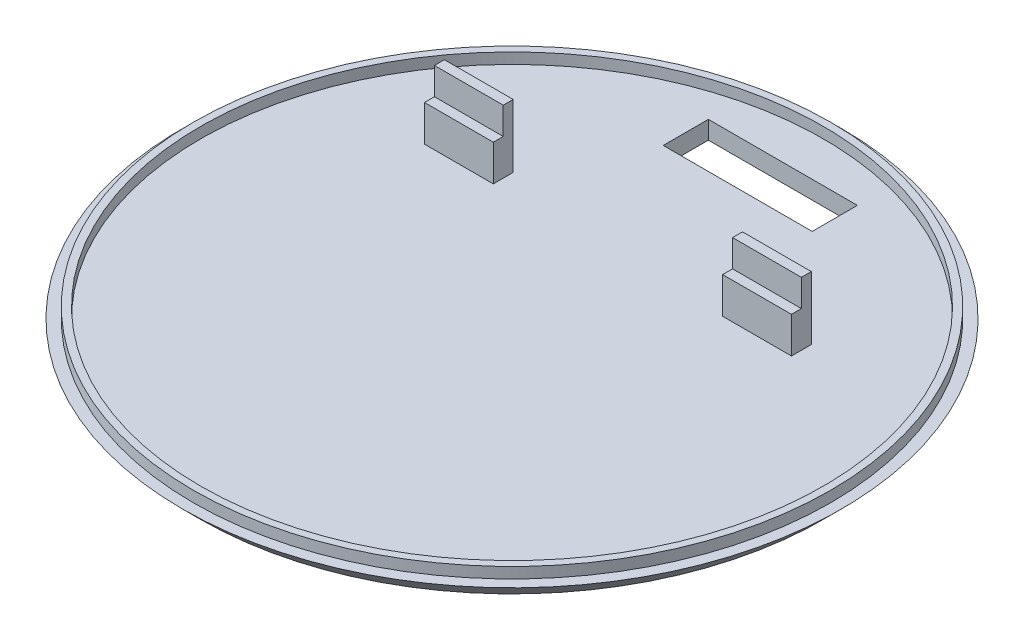
SolidWorks part; units mm, degrees
ref_plane "Front Plane" through (0, 0, 0) normal (0, 0, 1) x (1, 0, 0)
ref_plane "Top Plane" through (0, 0, 0) normal (0, 1, 0) x (1, 0, 0)
ref_plane "Right Plane" through (0, 0, 0) normal (1, 0, 0) x (0, 0, -1)
sketch "Sketch2" plane through (0, 0, 0) normal (0, 0, 1) x (1, 0, 0)
  line L0 (0, 31.7066) -> (0, -15.6367) construction
  line L1 (0, 0) -> (36.5, 0)
  line L2 (36.5, 0) -> (34.5, -2)
  line L3 (34.5, -2) -> (0, -2)
  line L4 (0, -2) -> (0, 0)
  line L6 (35.3, 0) -> (34.5, 0)
  line L7 (35.3, 0) -> (35.3, 1.2)
  line L8 (35.3, 1.2) -> (34.5, 1.2)
  line L9 (34.5, 0) -> (34.5, 1.2)
  dimension "D1" = 36.5
  dimension "D2" = 135
  dimension "D3" = 2
  dimension "D4" = 0.8
  dimension "D5" = 1.2
  dimension "D6" = 1.2
revolve "Revolve1" add sketch "Sketch2" angle 360 about L0
sketch "Sketch3" plane through (0, 0, 0) normal (0, 1, 0) x (1, 0, 0)
  line L1 (-8.25, 25) -> (8.25, 25)
  line L2 (-8.25, 25) -> (-8.25, 30)
  line L3 (-8.25, 30) -> (8.25, 30)
  line L4 (8.25, 25) -> (8.25, 30)
  dimension "D1" = 5
  dimension "D2" = 16.5
  dimension "D3" = 25
  dimension "D4" = 8.25
extrude "Cut-Extrude2" cut sketch "Sketch3" against normal up to next
sketch "Sketch4" plane through (0, 0, 0) normal (0, 1, 0) x (1, 0, 0)
  line L1 (-21.59, 14.1) -> (-13.97, 14.1)
  line L2 (-21.59, 14.1) -> (-21.59, 11.9)
  line L3 (-21.59, 11.9) -> (-13.97, 11.9)
  line L4 (-13.97, 14.1) -> (-13.97, 11.9)
  line L5 (11.43, 14.1) -> (19.05, 14.1)
  line L6 (11.43, 14.1) -> (11.43, 11.9)
  line L7 (11.43, 11.9) -> (19.05, 11.9)
  line L8 (19.05, 14.1) -> (19.05, 11.9)
  point P8 (15.24, 11.9)
  point P10 (-17.78, 11.9)
  point P11 (11.43, 13)
  dimension "D1" = 7.62
  dimension "D2" = 7.62
  dimension "D3" = 2.2
  dimension "D4" = 2.2
  dimension "D5" = 13
  dimension "D6" = 15.24
  dimension "D7" = 17.78
extrude "Boss-Extrude1" add sketch "Sketch4" along normal blind 4
sketch "Sketch5" plane through (0, 4, 0) normal (0, 1, 0) x (1, 0, 0)
  line L0 (-13.97, 11.9) -> (-13.97, 14.1) construction
  line L1 (-21.59, 14.1) -> (-13.97, 14.1)
  line L2 (-21.59, 14.1) -> (-21.59, 13)
  line L3 (-21.59, 13) -> (-13.97, 13)
  line L4 (-13.97, 14.1) -> (-13.97, 13)
  line L5 (19.05, 11.9) -> (19.05, 14.1) construction
  line L6 (11.43, 14.1) -> (19.05, 14.1)
  line L7 (11.43, 14.1) -> (11.43, 13)
  line L8 (11.43, 13) -> (19.05, 13)
  line L9 (19.05, 14.1) -> (19.05, 13)
extrude "Boss-Extrude2" add sketch "Sketch5" along normal blind 3
